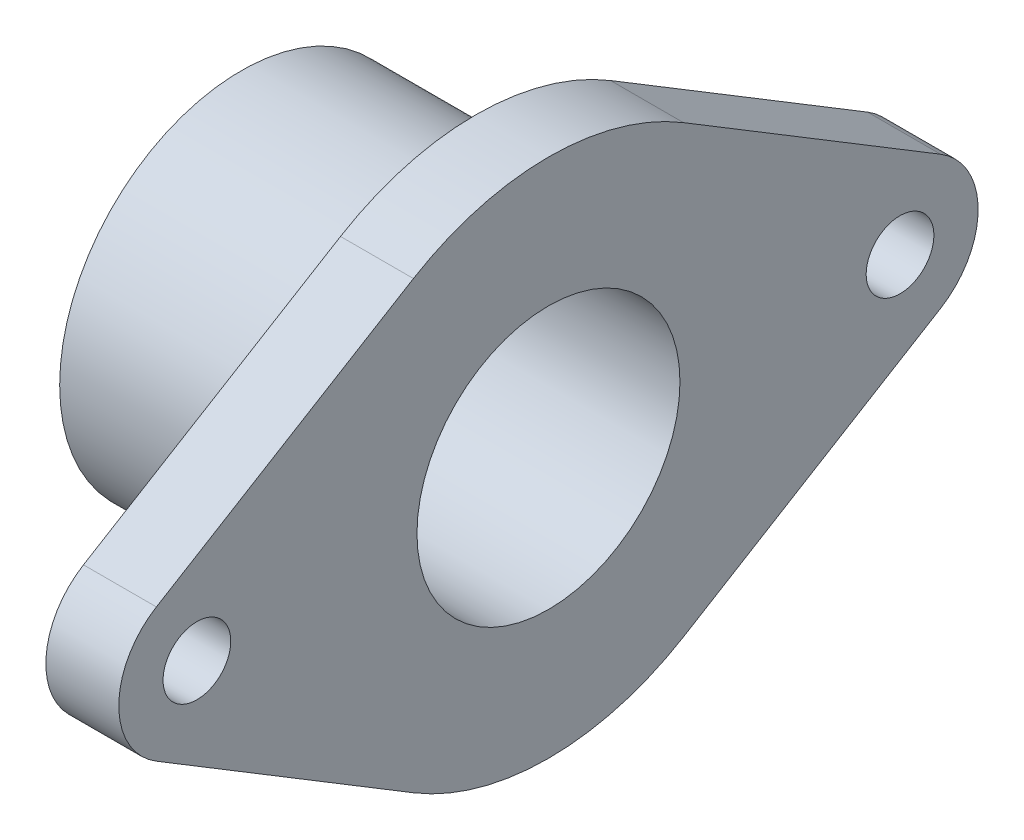
SolidWorks part; units mm, degrees
material "ASTM A36"
ref_plane "Front Plane" through (0, 0, 0) normal (0, 0, 1) x (1, 0, 0)
ref_plane "Top Plane" through (0, 0, 0) normal (0, 1, 0) x (1, 0, 0)
ref_plane "Right Plane" through (0, 0, 0) normal (1, 0, 0) x (0, 0, -1)
sketch "Sketch1" plane through (0, 0, 0) normal (1, 0, 0) x (0, 0, -1)
  line L0 (-25.9259, 42.7533) -> (-75.2778, 12.826)
  line L1 (25.9259, 42.7533) -> (75.2778, 12.826)
  line L2 (-75.2778, -12.826) -> (-25.9259, -42.7533)
  line L3 (75.2778, -12.826) -> (25.9259, -42.7533)
  arc A0 (25.9259, 42.7533) -> (-25.9259, 42.7533) centre (0, 0) ccw
  arc A1 (-75.2778, 12.826) -> (-75.2778, -12.826) centre (-67.5, 0) ccw
  arc A2 (75.2778, -12.826) -> (75.2778, 12.826) centre (67.5, 0) ccw
  arc A3 (-25.9259, -42.7533) -> (25.9259, -42.7533) centre (0, 0) ccw
  dimension "D1" = 100
  dimension "D2" = 30
  dimension "D3" = 30
  dimension "D4" = 67.5
  dimension "D5" = 67.5
extrude "Boss-Extrude1" add sketch "Sketch1" along normal blind 14
sketch "Sketch2" plane through (0, 0, 0) normal (-1, 0, 0) x (0, 0, 1)
  circle A0 centre (67.5, 0) radius 6.5
  circle A1 centre (-67.5, 0) radius 6.5
  dimension "D1" = 13
  dimension "D2" = 13
extrude "Cut-Extrude1" cut sketch "Sketch2" against normal through all
sketch "Sketch3" plane through (0, 0, 0) normal (-1, 0, 0) x (0, 0, 1)
  circle A0 centre (0, 0) radius 25.25
  dimension "D1" = 50.5
extrude "Cut-Extrude2" cut sketch "Sketch3" against normal through all
sketch "Sketch4" plane through (0, 0, 0) normal (-1, 0, 0) x (0, 0, 1)
  circle A0 centre (0, 0) radius 25.25
  circle A1 centre (0, 0) radius 34.85
  dimension "D1" = 50.5
  dimension "D2" = 69.7
extrude "Boss-Extrude2" add sketch "Sketch4" along normal blind 45
sketch "Sketch5" plane through (0, 0, 0) normal (0, 1, 0) x (1, 0, 0)
  line L0 (0, 34.85) -> (-5, 34.85)
  line L1 (0, 34.85) -> (-45, 34.85) construction
  line L2 (-5, 34.85) -> (0, 41.85)
  line L3 (0, 75.2778) -> (0, 25.9259) construction
  line L4 (0, 41.85) -> (0, 34.85)
  line L5 (0, 0) -> (-83.9507, 0) construction
  dimension "D1" = 5
  dimension "D2" = 7
revolve "Revolve1" add sketch "Sketch5" angle 360 about L5
